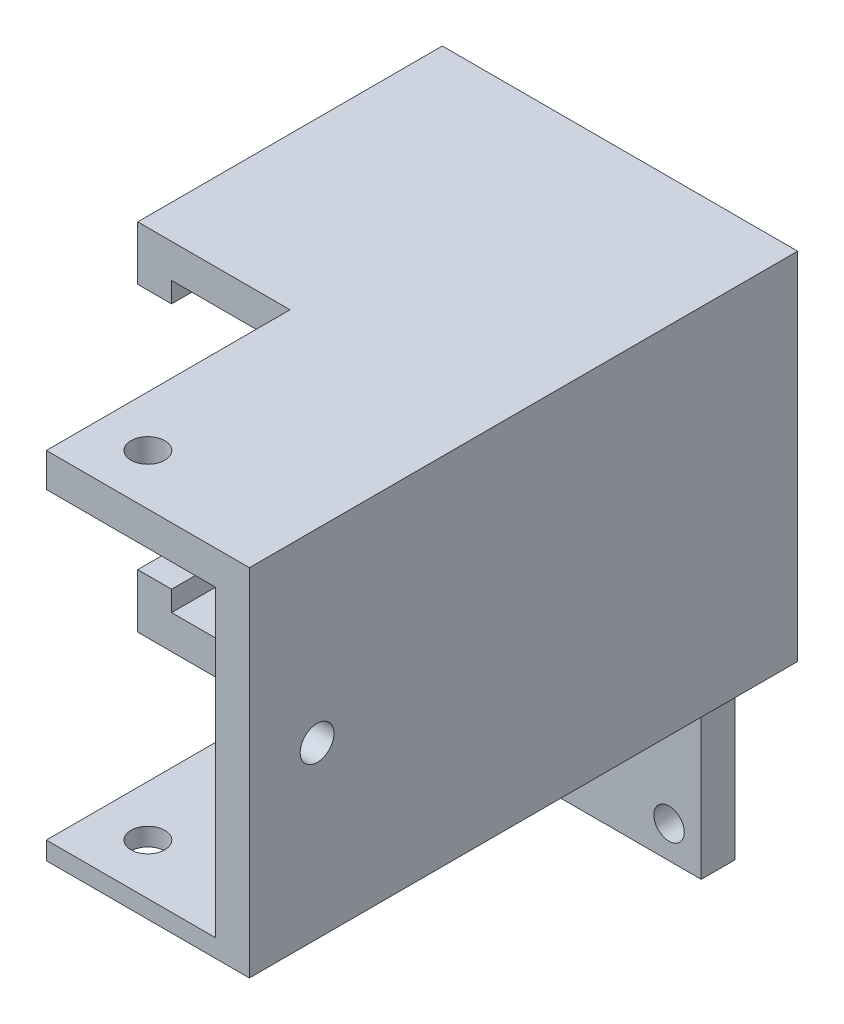
SolidWorks part; units mm, degrees
ref_plane "Front Plane" through (0, 0, 0) normal (0, 0, 1) x (1, 0, 0)
ref_plane "Top Plane" through (0, 0, 0) normal (0, 1, 0) x (1, 0, 0)
ref_plane "Right Plane" through (0, 0, 0) normal (1, 0, 0) x (0, 0, -1)
sketch "Sketch1" plane through (0, 0, 0) normal (0, 0, 1) x (1, 0, 0)
  line L0 (0, 30) -> (-9.25, 30)
  line L1 (0, 0) -> (34, 0)
  line L2 (0, 0) -> (0, 30)
  line L4 (34, 0) -> (34, 30)
  line L5 (-9.25, 30) -> (-9.25, 82.5)
  line L6 (-9.25, 82.5) -> (43.25, 82.5)
  line L7 (43.25, 82.5) -> (43.25, 30)
  line L8 (34, 30) -> (43.25, 30)
  circle A0 centre (4.75, 25.25) radius 2.25
  circle A1 centre (29.25, 25.25) radius 2.25
  circle A2 centre (29.25, 4.75) radius 2.25
  circle A3 centre (4.75, 4.75) radius 2.25
  dimension "D3" = 4.5
  dimension "D6" = 4.5
  dimension "D13" = 4.5
  dimension "D14" = 4.5
  dimension "D15" = 52.5
  dimension "D16" = 9.25
  dimension "D1" = 30
  dimension "D2" = 34
  dimension "D4" = 4.75
  dimension "D8" = 4.75
  dimension "D9" = 4.75
  dimension "D10" = 4.75
  dimension "D11" = 4.75
  dimension "D12" = 4.75
  dimension "D17" = 52.5
extrude "Boss-Extrude1" add sketch "Sketch1" along normal blind 5
sketch "Sketch2" plane through (0, 0, 5) normal (0, 0, 1) x (1, 0, 0)
  line L1 (-9.25, 82.5) -> (43.25, 82.5)
  line L2 (-9.25, 82.5) -> (-9.25, 30)
  line L3 (-9.25, 30) -> (43.25, 30)
  line L4 (43.25, 82.5) -> (43.25, 30)
  line L5 (-4.25, 77.5) -> (38.25, 77.5)
  line L6 (-4.25, 77.5) -> (-4.25, 35)
  line L7 (-4.25, 35) -> (38.25, 35)
  line L8 (38.25, 77.5) -> (38.25, 35)
  dimension "D1" = 5
  dimension "D2" = 5
  dimension "D3" = 5
  dimension "D4" = 5
extrude "Boss-Extrude2" add sketch "Sketch2" along normal blind 40
sketch "Sketch5" plane through (0, 0, 45) normal (0, 0, 1) x (1, 0, 0)
  line L0 (-9.25, 30) -> (43.25, 30) construction
  line L6 (43.25, 82.5) -> (-9.25, 82.5) construction
  line L7 (43.25, 82.5) -> (43.25, 30)
  line L8 (13.25, 82.5) -> (13.25, 77.5)
  line L9 (38.25, 77.5) -> (-4.25, 77.5) construction
  line L10 (13.25, 77.5) -> (38.25, 77.5)
  line L12 (0, 30) -> (34, 30) construction
  line L13 (13.25, 30) -> (13.25, 35)
  line L14 (-4.25, 35) -> (38.25, 35) construction
  line L15 (13.25, 35) -> (38.25, 35)
  line L16 (13.25, 82.5) -> (43.25, 82.5)
  line L17 (43.25, 30) -> (13.25, 30)
  line L18 (38.25, 77.5) -> (38.25, 35)
  dimension "D1" = 25
  dimension "D2" = 0
  dimension "D3" = 5
extrude "Boss-Extrude3" add sketch "Sketch5" along normal blind 36
sketch "Sketch6" plane through (0, 77.5, 0) normal (0, -1, 0) x (1, 0, 0)
  line L0 (13.25, 81) -> (13.25, 45) construction
  line L1 (13.25, 81) -> (38.25, 81) construction
  circle A0 centre (20.75, 73.5) radius 2.5
  dimension "D1" = 5
  dimension "D2" = 7.5
  dimension "D3" = 7.5
extrude "Cut-Extrude2" cut sketch "Sketch6" against normal through all both and the other way through all
sketch "Sketch7" plane through (43.25, 0, 0) normal (1, 0, 0) x (0, 0, -1)
  line L0 (-81, 30) -> (-81, 82.5) construction
  line L2 (-81, 82.5) -> (0, 82.5) construction
  circle A0 centre (-71, 55.075) radius 2.5
  dimension "D1" = 5
  dimension "D2" = 10
  dimension "D3" = 27.425
extrude "Cut-Extrude3" cut sketch "Sketch7" against normal through all both
sketch "Sketch8" plane through (-9.25, 0, 0) normal (-1, 0, 0) x (0, 0, 1)
  line L0 (45, 82.5) -> (45, 30) construction
  line L1 (45, 74.5) -> (5, 74.5)
  line L2 (45, 74.5) -> (45, 38)
  line L3 (45, 38) -> (5, 38)
  line L4 (5, 74.5) -> (5, 38)
  line L5 (45, 82.5) -> (0, 82.5) construction
  line L6 (45, 30) -> (0, 30) construction
  line L7 (0, 82.5) -> (0, 30) construction
  point P8 (22.5, 82.5)
  dimension "D1" = 8
  dimension "D2" = 8
  dimension "D3" = 5
extrude "Cut-Extrude4" cut sketch "Sketch8" against normal blind 24
sketch "Sketch9" plane through (0, 35, 0) normal (0, 1, 0) x (1, 0, 0)
  line L0 (38.25, -81) -> (38.25, -5) construction
  line L1 (13.25, -81) -> (38.25, -81)
  line L2 (13.25, -81) -> (13.25, -55.4806)
  line L3 (13.25, -55.4806) -> (38.25, -55.4806)
  line L4 (38.25, -81) -> (38.25, -55.4806)
extrude "Cut-Extrude5" cut sketch "Sketch9" against normal blind 2.35
